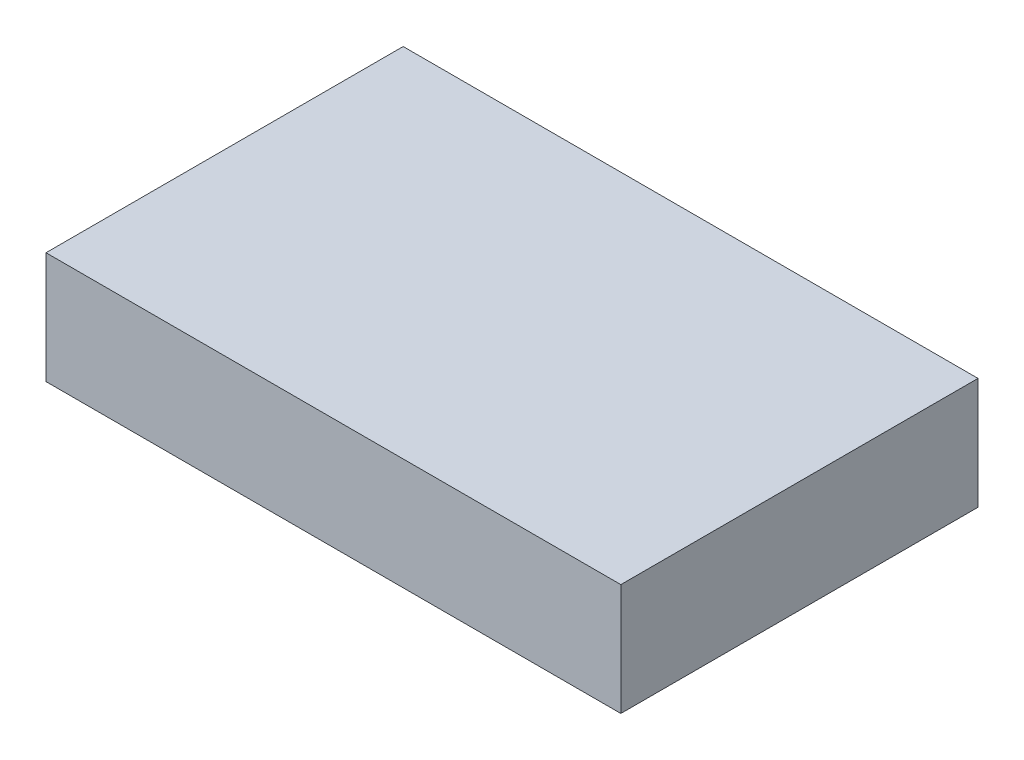
SolidWorks part; units mm, degrees
ref_plane "Front Plane" through (0, 0, 0) normal (0, 0, 1) x (1, 0, 0)
ref_plane "Top Plane" through (0, 0, 0) normal (0, 1, 0) x (1, 0, 0)
ref_plane "Right Plane" through (0, 0, 0) normal (1, 0, 0) x (0, 0, -1)
sketch "Sketch1" plane through (0, 0, 0) normal (0, 1, 0) x (1, 0, 0)
  line L1 (-6.5405, -4.064) -> (6.5405, -4.064)
  line L2 (-6.5405, -4.064) -> (-6.5405, 4.064)
  line L3 (-6.5405, 4.064) -> (6.5405, 4.064)
  line L4 (6.5405, -4.064) -> (6.5405, 4.064)
  line L5 (-6.5405, -4.064) -> (6.5405, 4.064) construction
  line L6 (-6.5405, 4.064) -> (6.5405, -4.064) construction
  point P0 (0, 0)
  dimension "D1" = 8.128
  dimension "D2" = 13.081
extrude "Boss-Extrude1" add sketch "Sketch1" along normal blind 2.54
